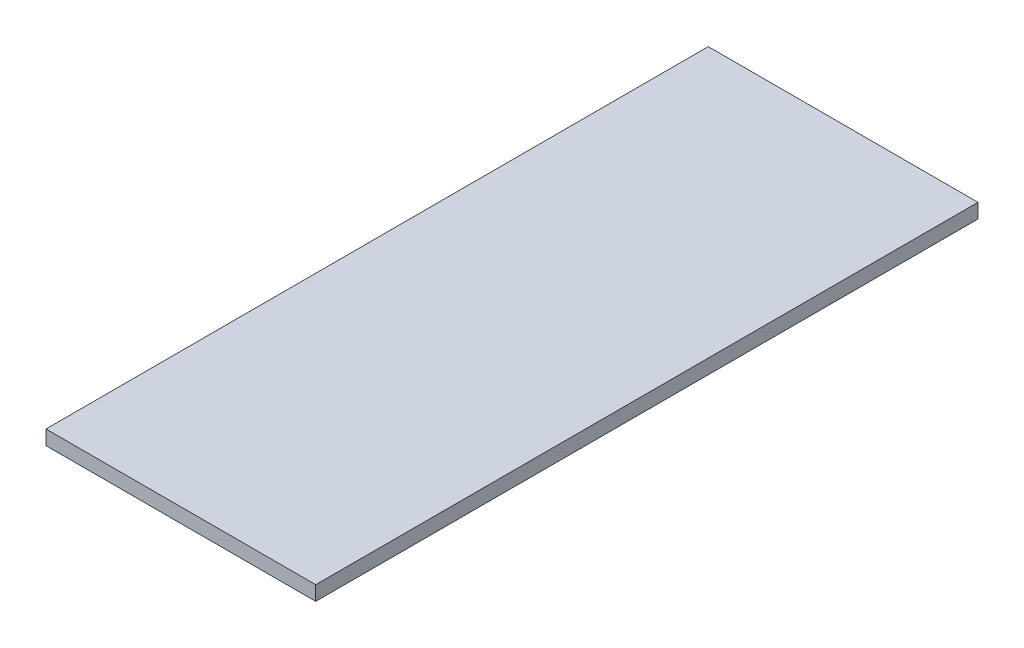
SolidWorks part; units mm, degrees
ref_plane "Front Plane" through (0, 0, 0) normal (0, 0, 1) x (1, 0, 0)
ref_plane "Top Plane" through (0, 0, 0) normal (0, 1, 0) x (1, 0, 0)
ref_plane "Right Plane" through (0, 0, 0) normal (1, 0, 0) x (0, 0, -1)
sketch "Sketch1" plane through (0, 0, 0) normal (0, 1, 0) x (1, 0, 0)
  line L0 (-26.0602, 31.6251) -> (85.9398, 31.6251)
  line L1 (85.9398, 31.6251) -> (85.9398, -243.3749)
  line L2 (85.9398, -243.3749) -> (-26.0602, -243.3749)
  line L3 (-26.0602, -243.3749) -> (-26.0602, 31.6251)
extrude "Boss-Extrude1" add sketch "Sketch1" along normal blind 6
